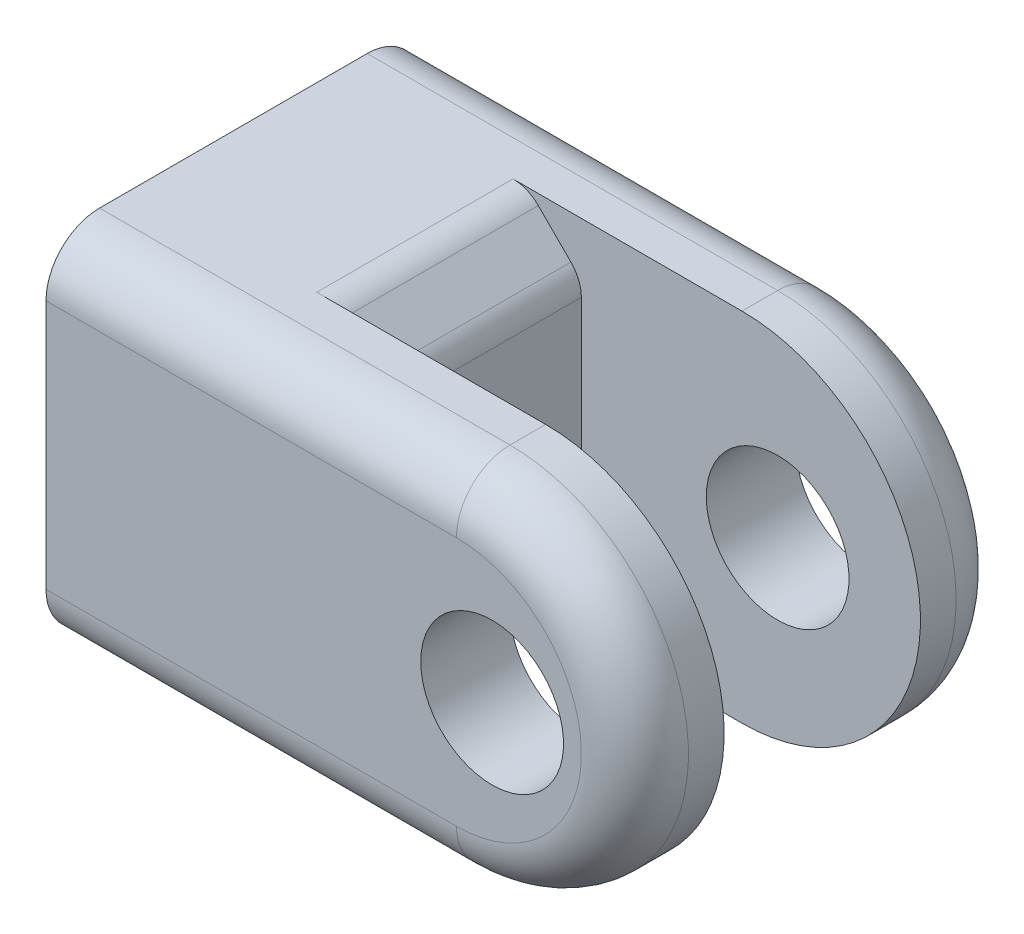
SolidWorks part; units mm, degrees
material "2024 Alloy"
ref_plane "Front Plane" through (0, 0, 0) normal (0, 0, 1) x (1, 0, 0)
ref_plane "Top Plane" through (0, 0, 0) normal (0, 1, 0) x (1, 0, 0)
ref_plane "Right Plane" through (0, 0, 0) normal (1, 0, 0) x (0, 0, -1)
sketch "Sketch1" plane through (0, 0, 0) normal (0, 0, 1) x (1, 0, 0)
  line L0 (0, 0) -> (0, 20)
  line L1 (0, 20) -> (25, 20) construction
  line L2 (25, 20) -> (25, 0) construction
  line L3 (25, 0) -> (0, 0) construction
  line L4 (0, 20) -> (23, 20)
  line L5 (0, 0) -> (23, 0)
  circle A1 centre (25, 10) radius 4
  arc A3 (23, 20) -> (23, 0) centre (23, 10) cw
  dimension "D2" = 8
  dimension "D3" = 20
  dimension "D4" = 2
  dimension "D5" = 10
  dimension "D1" = 25
extrude "Boss-Extrude1" add sketch "Sketch1" along normal blind 21
sketch "Sketch2" plane through (0, 20, 0) normal (0, 1, 0) x (1, 0, 0)
  line L1 (14, -16) -> (33, -16)
  line L2 (14, -16) -> (14, -5)
  line L3 (14, -5) -> (33, -5)
  line L4 (33, -16) -> (33, -5)
  line L5 (14, -16) -> (33, -5) construction
  line L6 (14, -5) -> (33, -16) construction
  line L7 (0, -10.5) -> (33, -10.5) construction
  line L10 (33, -21) -> (33, 0) construction
  line L11 (0, -21) -> (0, 0) construction
  point P0 (23.5, -10.5)
  dimension "D1" = 11
  dimension "D2" = 14
extrude "Cut-Extrude1" cut sketch "Sketch2" against normal up to surface (20 mm away) up to face at (11.5, 0, 10.5)
sketch "Sketch3" plane through (0, 0, 0) normal (-1, 0, 0) x (0, 0, 1)
  line L0 (0, 20) -> (21, 0) construction
  circle A0 centre (10.5, 10) radius 8.5
  dimension "D1" = 17
extrude "Cut-Extrude2" cut sketch "Sketch3" against normal offset from surface (12 mm away) 2 up to face at (14, 10, 10.5)
hole_wizard "M2x0.4 Tapped Hole1" positions "Sketch5" profile "Sketch4" tap size "M2x0.4" standard "ANSI Metric"
sketch "Sketch5" plane through (0, 0, 0) normal (-1, 0, 0) x (0, 0, 1)
  line L2 (2, 17.5) -> (19, 17.5)
  line L3 (2, 17.5) -> (2, 2.5)
  line L4 (2, 2.5) -> (19, 2.5)
  line L5 (19, 17.5) -> (19, 2.5)
  line L6 (2, 17.5) -> (19, 2.5) construction
  line L7 (2, 2.5) -> (19, 17.5) construction
  circle A3 centre (10.5, 10) radius 8.5 construction
  circle A4 centre (10.5, 10) radius 8.5 construction
  point P0 (2, 17.5)
  point P2 (19, 17.5)
  point P4 (19, 2.5)
  point P6 (2, 2.5)
  dimension "D1" = 15
  dimension "D2" = 17
sketch "Sketch4" plane through (0, 17.5, 2) normal (0, 1, 0) x (0, 0, 1)
  line L0 (0, 0) -> (0, 8.4807)
  line L1 (0, 8.4807) -> (0.8, 8)
  line L2 (0.8, 8) -> (0.8, 0)
  line L5 (0.8, 0) -> (0, 0)
  line L10 (0, 8.4807) -> (-0.8, 8) construction
  line L11 (0, -6.35) -> (0, 107.95) construction
  dimension "Tap Drill Dia." = 1.6
  dimension "Tap Drill Depth" = 8
  dimension "Drill Angle" = 118
cosmetic thread "Hole Thread1" parameters "D1"=7.6, "D2"=2
cosmetic thread "Hole Thread2" parameters "D1"=7.6, "D2"=2
cosmetic thread "Hole Thread3" parameters "D1"=7.6, "D2"=2
cosmetic thread "Hole Thread4" parameters "D1"=7.6, "D2"=2
fillet "Fillet2" radius 3 6 edges at (11.5, 20, 21) (33, 10, 21) (11.5, 20, 0) (33, 10, 0) (11.5, 0, 21) (11.5, 0, 0)
chamfer "Chamfer1" distance 3 angle 45 2 edges at (14, 0, 10.5) (14, 20, 10.5)
fillet "Fillet3" radius 2 4 edges at (11, 20, 10.5) (14, 17, 10.5) (14, 3, 10.5) (11, 0, 10.5)
